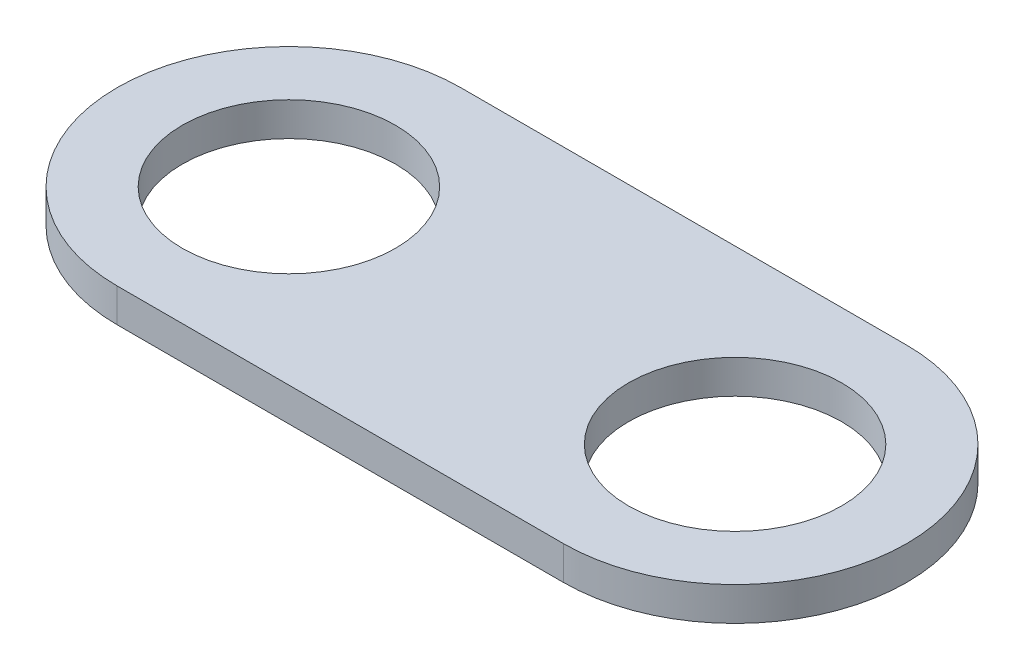
SolidWorks part; units mm, degrees
ref_plane "Front Plane" through (0, 0, 0) normal (0, 0, 1) x (1, 0, 0)
ref_plane "Top Plane" through (0, 0, 0) normal (0, 1, 0) x (1, 0, 0)
ref_plane "Right Plane" through (0, 0, 0) normal (1, 0, 0) x (0, 0, -1)
sketch "Sketch1" plane through (0, 0, 0) normal (0, 1, 0) x (1, 0, 0)
  line L0 (19.8792, 0) -> (-19.8792, 0)
  line L1 (-19.8792, -30.6106) -> (19.8792, -30.6106)
  arc A0 (-19.8792, 0) -> (-19.8792, -30.6106) centre (-19.8792, -15.3053) ccw
  arc A1 (19.8792, -30.6106) -> (19.8792, 0) centre (19.8792, -15.3053) ccw
  point P4 (0, 0)
  dimension "D1" = 39.7583
  dimension "D2" = 30.6106
extrude "Boss-Extrude1" add sketch "Sketch1" along normal blind 3
sketch "Sketch2" plane through (0, 3, 0) normal (0, 1, 0) x (1, 0, 0)
  line L0 (-19.8792, 0) -> (-19.8792, -30.6106) construction
  line L1 (0, 0) -> (0, -30.6106) construction
  line L2 (-19.8792, -30.6106) -> (19.8792, -30.6106) construction
  circle A0 centre (-19.8792, -15.3053) radius 9.5
  circle A2 centre (19.8792, -15.3053) radius 9.5
  dimension "D1" = 19
extrude "Cut-Extrude1" cut sketch "Sketch2" against normal through all
